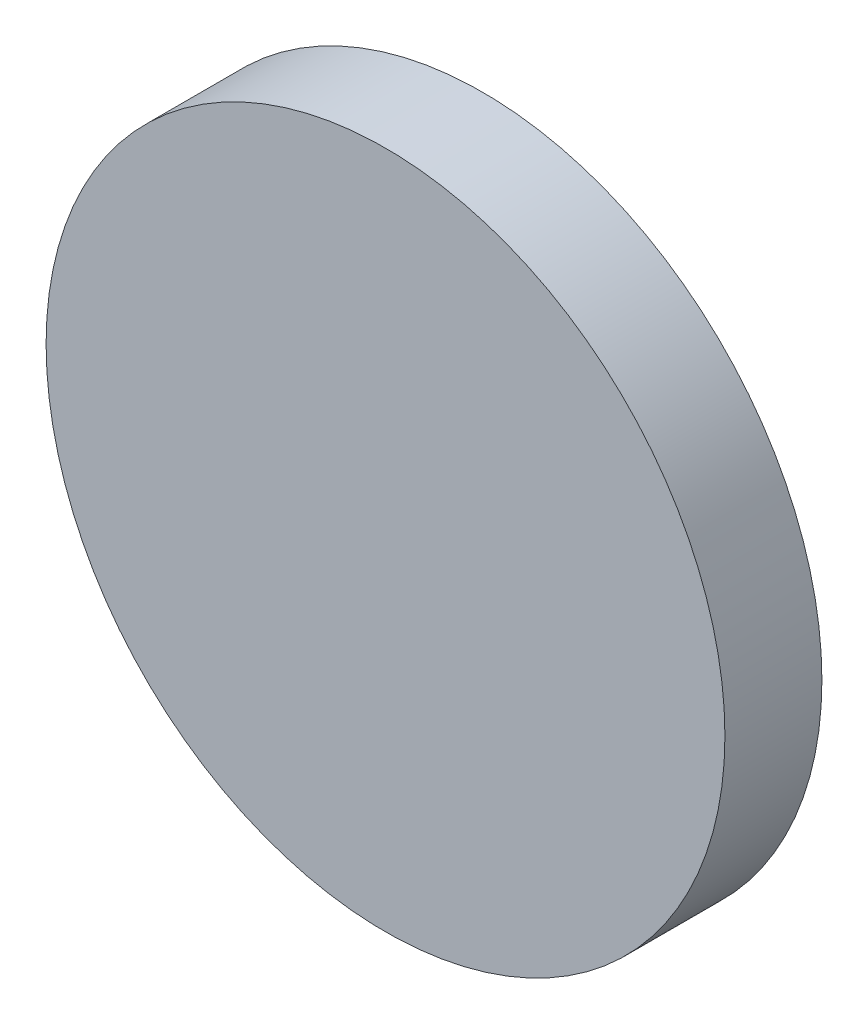
SolidWorks part; units mm, degrees
ref_plane "Front Plane" through (0, 0, 0) normal (0, 0, 1) x (1, 0, 0)
ref_plane "Top Plane" through (0, 0, 0) normal (0, 1, 0) x (1, 0, 0)
ref_plane "Right Plane" through (0, 0, 0) normal (1, 0, 0) x (0, 0, -1)
sketch "Sketch1" plane through (0, 0, 0) normal (0, 0, 1) x (1, 0, 0)
  circle A0 centre (0, 0) radius 40.25
  circle A1 centre (0, 0) radius 42
extrude "Boss-Extrude1" add sketch "Sketch1" along normal blind 10
sketch "Sketch2" plane through (0, 0, 10) normal (0, 0, 1) x (1, 0, 0)
  circle A1 centre (0, 0) radius 42
  circle A2 centre (0, 0) radius 42
  dimension "D1" = 0
extrude "Boss-Extrude2" add sketch "Sketch2" along normal blind 2
